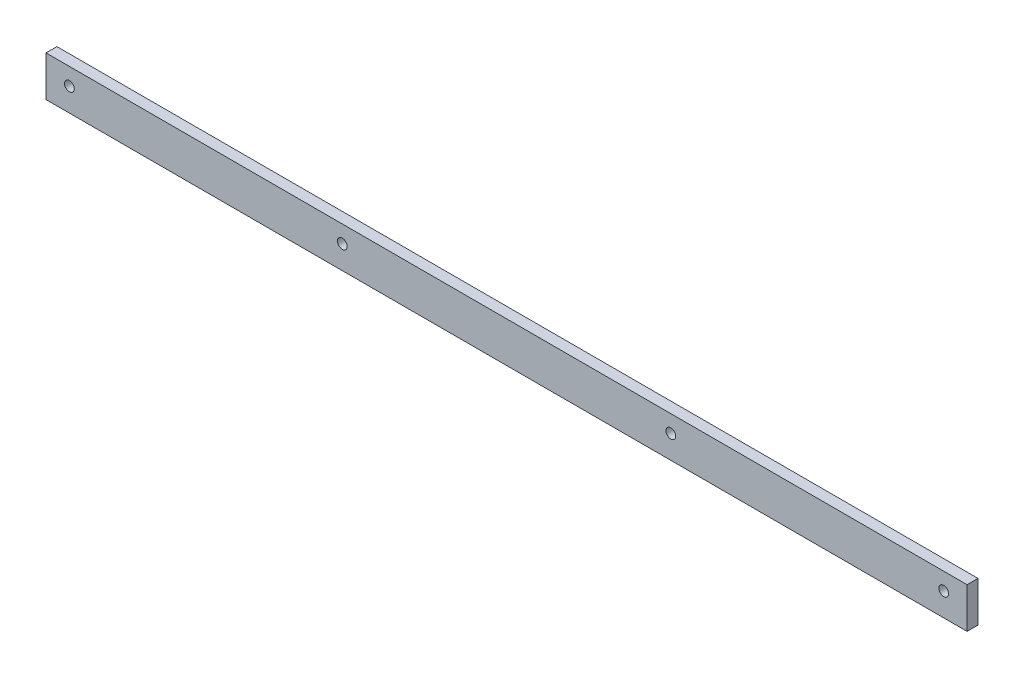
SolidWorks part; units mm, degrees
ref_plane "Front Plane" through (0, 0, 0) normal (0, 0, 1) x (1, 0, 0)
ref_plane "Top Plane" through (0, 0, 0) normal (0, 1, 0) x (1, 0, 0)
ref_plane "Right Plane" through (0, 0, 0) normal (1, 0, 0) x (0, 0, -1)
sketch "Sketch1" plane through (0, 0, 0) normal (0, 0, 1) x (1, 0, 0)
  line L1 (-134.32, 5.9) -> (134.32, 5.9)
  line L2 (-134.32, 5.9) -> (-134.32, -5.9)
  line L3 (-134.32, -5.9) -> (134.32, -5.9)
  line L4 (134.32, 5.9) -> (134.32, -5.9)
  line L5 (-134.32, 5.9) -> (134.32, -5.9) construction
  line L6 (-134.32, -5.9) -> (134.32, 5.9) construction
  point P0 (0, 0)
  dimension "D1" = 11.8
  dimension "D2" = 268.64
extrude "Boss-Extrude1" add sketch "Sketch1" along normal blind 3.18
sketch "Sketch3" plane through (0, 0, 0) normal (0, 0, 1) x (1, 0, 0)
  line L0 (127.5, 0.9) -> (126.075, 0.9) construction
  line L1 (47.91, 0.9) -> (-47.91, 0.9) construction
  line L2 (-47.91, 0.9) -> (-49.335, 0.9) construction
  line L3 (-126.075, 0.9) -> (-127.5, 0.9) construction
  line L4 (49.335, 0.9) -> (47.91, 0.9) construction
  line L9 (127.5, 0.9) -> (126.075, 0.9) construction
  line L10 (-47.91, 0.9) -> (-49.335, 0.9) construction
  line L11 (49.335, 0.9) -> (47.91, 0.9) construction
  line L12 (134.32, 5.9) -> (-134.32, 5.9) construction
  line L13 (-126.075, 0.9) -> (-127.5, 0.9) construction
  line L14 (47.91, 0.9) -> (127.5, 0.9) construction
  line L15 (-47.91, 0.9) -> (-127.5, 0.9) construction
  circle A4 centre (127.5, 0.9) radius 1.425
  circle A5 centre (47.91, 0.9) radius 1.425
  circle A6 centre (-47.91, 0.9) radius 1.425
  circle A7 centre (-127.5, 0.9) radius 1.425
  point P14 (0, 0.9)
  dimension "D4" = 2.85
  dimension "D1" = 79.59
  dimension "D2" = 95.82
  dimension "D3" = 79.59
  dimension "D7" = 5
extrude "Cut-Extrude1" cut sketch "Sketch3" along normal up to next contours A4 | A5 | A6 | A7
